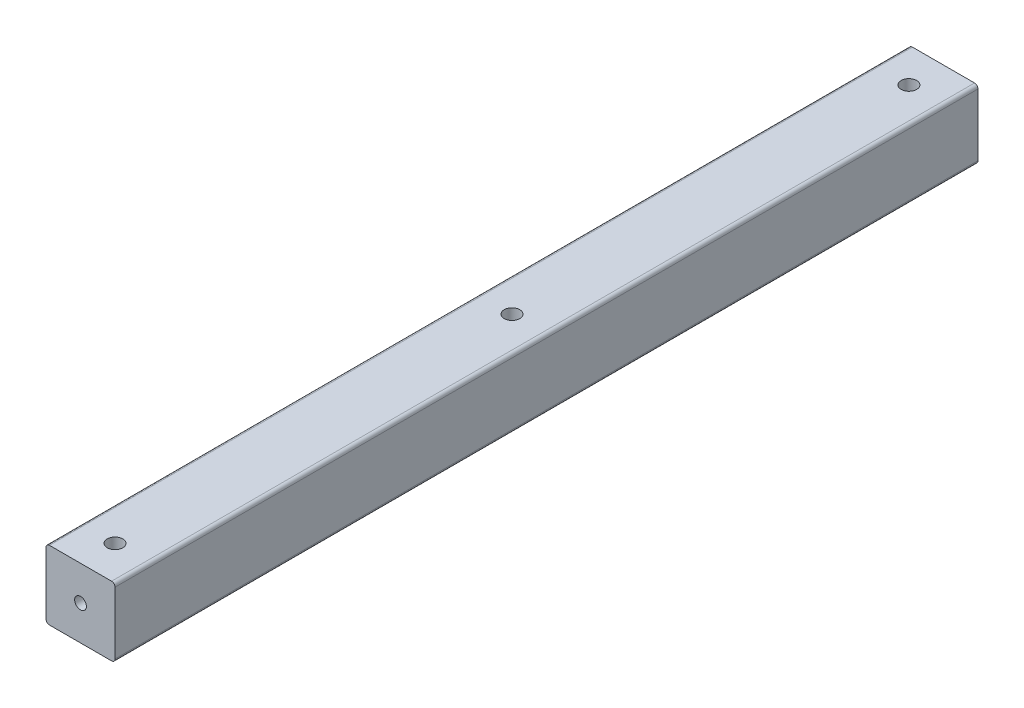
SolidWorks part; units mm, degrees
ref_plane "Front Plane" through (0, 0, 0) normal (0, 0, 1) x (1, 0, 0)
ref_plane "Top Plane" through (0, 0, 0) normal (0, 1, 0) x (1, 0, 0)
ref_plane "Right Plane" through (0, 0, 0) normal (1, 0, 0) x (0, 0, -1)
sketch "Sketch1" plane through (0, 0, 0) normal (0, 0, 1) x (1, 0, 0)
  line L1 (-20, -20) -> (20, -20)
  line L2 (-20, -20) -> (-20, 20)
  line L3 (-20, 20) -> (20, 20)
  line L4 (20, -20) -> (20, 20)
  line L5 (-20, -20) -> (20, 20) construction
  line L6 (-20, 20) -> (20, -20) construction
  circle A0 centre (0, 0) radius 2.5
  point P0 (0, 0)
  dimension "D3" = 5
  dimension "D1" = 40
  dimension "D2" = 40
extrude "Boss-Extrude1" add sketch "Sketch1" along normal mid plane 500
fillet "Fillet1" radius 2 4 edges at (20, -20, 0) (-20, -20, 0) (-20, 20, 0) (20, 20, 0)
sketch "Sketch2" plane through (0, 20, 0) normal (0, 1, 0) x (1, 0, 0)
  line L0 (0, 958.3172) -> (0, -945.7078) construction
  line L2 (18, 250) -> (-18, 250) construction
  line L3 (18, -250) -> (-18, -250) construction
  point P3 (0, -350)
  point P4 (0, 350)
  dimension "D1" = 600
  dimension "D2" = 600
hole_wizard "Ø4.5 (4.5) Diameter Hole1" positions "Sketch3" profile "Sketch4" hole size "Ø4.5" standard "ISO"
sketch "Sketch3" plane through (0, 20, 0) normal (0, 1, 0) x (1, 0, 0)
  point P0 (0, -300)
  point P3 (0, 300)
sketch "Sketch4" plane through (0, 20, 300) normal (1, 0, 0) x (0, 0, 1)
  line L0 (0, 0) -> (0, 40)
  line L1 (0, 40) -> (2.25, 40)
  line L2 (2.25, 40) -> (2.25, 0)
  line L5 (2.25, 0) -> (0, 0)
  line L11 (0, -6.35) -> (0, 107.95) construction
  dimension "Thru Hole Dia." = 4.5
  dimension "Thru Hole Depth" = 40
sketch "Sketch5" plane through (0, -20, 0) normal (0, -1, 0) x (1, 0, 0)
  line L0 (0, 250) -> (0, -1000.0028) construction
  line L1 (-18, 250) -> (18, 250) construction
  line L2 (-18, -250) -> (18, -250) construction
  point P4 (0, 230)
  point P5 (0, 500)
  point P6 (0, 0)
  point P7 (0, -500)
  point P8 (0, -230)
  dimension "D1" = 500
  dimension "D2" = 500
  dimension "D3" = 20
  dimension "D4" = 20
hole_wizard "CBORE for M8 Hex Socket Head Cap Screw1" positions "Sketch6" profile "Sketch7" counterbore size "M8" standard "ISO" end condition through all
sketch "Sketch6" plane through (0, -20, 0) normal (0, -1, 0) x (-1, 0, 0)
  point P0 (0, 500)
  point P3 (0, 0)
  point P6 (0, -500)
  point P9 (0, 230)
  point P12 (0, -230)
sketch "Sketch7" plane through (0, -20, -500) normal (1, 0, 0) x (0, 0, -1)
  line L0 (0, 0) -> (0, 40)
  line L1 (0, 40) -> (4.5, 40)
  line L3 (4.5, 40) -> (4.5, 8.6)
  line L4 (4.5, 8.6) -> (7.5, 8.6)
  line L5 (7.5, 8.6) -> (7.5, 0)
  line L7 (7.5, 0) -> (0, 0)
  line L11 (0, -6.35) -> (0, 107.95) construction
  dimension "Thru Hole Dia." = 9
  dimension "Thru Hole Depth" = 40
  dimension "C'Bore Dia." = 15
  dimension "C'Bore Depth" = 8.6
hole_wizard "M8x1.25 Tapped Hole1" positions "Sketch8" profile "Sketch9" tap size "M8x1.25" standard "ANSI Metric"
sketch "Sketch8" plane through (0, 0, 250) normal (0, 0, 1) x (1, 0, 0)
  point P0 (0, 0)
sketch "Sketch9" plane through (0, 0, 250) normal (1, 0, 0) x (0, -1, 0)
  line L0 (0, 0) -> (0, 29.7929)
  line L1 (0, 29.7929) -> (3.4, 27.75)
  line L2 (3.4, 27.75) -> (3.4, 0)
  line L5 (3.4, 0) -> (0, 0)
  line L10 (0, 29.7929) -> (-3.4, 27.75) construction
  line L11 (0, -6.35) -> (0, 107.95) construction
  dimension "Tap Drill Dia." = 6.8
  dimension "Tap Drill Depth" = 27.75
  dimension "Drill Angle" = 118
cosmetic thread "Hole Thread1" parameters "D1"=24, "D2"=8
mirror "Mirror1" about plane through (0, 0, 0) normal (0, 0, 1) of "M8x1.25 Tapped Hole1"
cosmetic thread "Hole Thread2" parameters "D1"=24, "D2"=8
